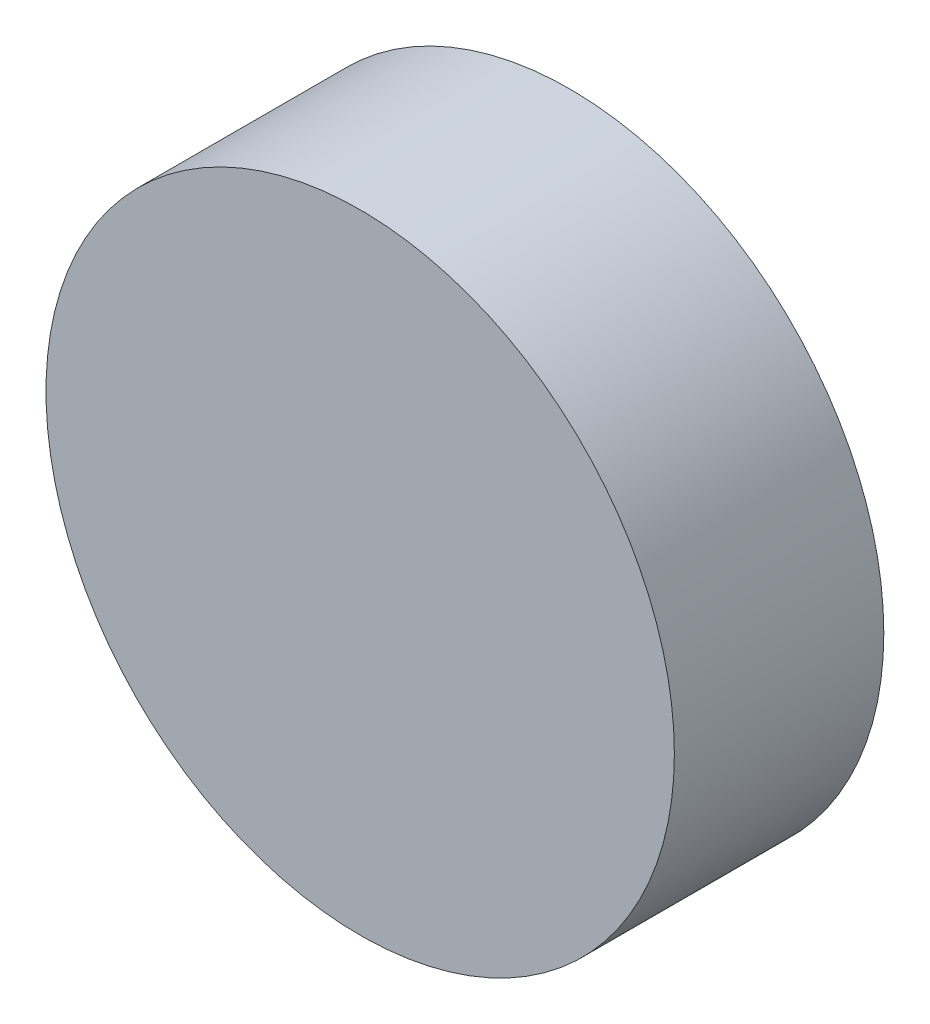
SolidWorks part; units mm, degrees
ref_plane "Front Plane" through (0, 0, 0) normal (0, 0, 1) x (1, 0, 0)
ref_plane "Top Plane" through (0, 0, 0) normal (0, 1, 0) x (1, 0, 0)
ref_plane "Right Plane" through (0, 0, 0) normal (1, 0, 0) x (0, 0, -1)
sketch "Sketch1" plane through (0, 0, 0) normal (0, 0, 1) x (1, 0, 0)
  circle A0 centre (0, 0) radius 3
  dimension "D1" = 6
extrude "Boss-Extrude1" add sketch "Sketch1" along normal blind 2
